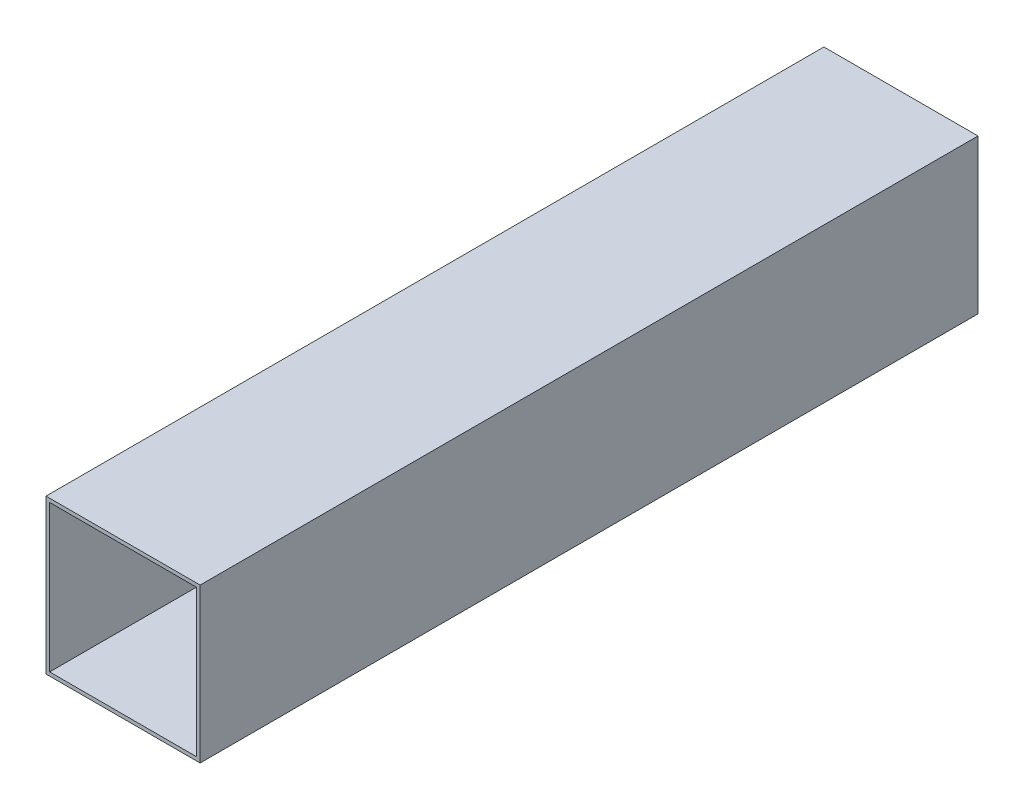
SolidWorks part; units mm, degrees
ref_plane "Front Plane" through (0, 0, 0) normal (0, 0, 1) x (1, 0, 0)
ref_plane "Top Plane" through (0, 0, 0) normal (0, 1, 0) x (1, 0, 0)
ref_plane "Right Plane" through (0, 0, 0) normal (1, 0, 0) x (0, 0, -1)
sketch "Sketch2" plane through (0, 0, 0) normal (0, 0, 1) x (1, 0, 0)
  line L1 (-50, -50) -> (50, -50)
  line L2 (-50, -50) -> (-50, 50)
  line L3 (-50, 50) -> (50, 50)
  line L4 (50, -50) -> (50, 50)
  line L5 (-50, -50) -> (50, 50) construction
  line L6 (-50, 50) -> (50, -50) construction
  line L7 (-52.5, 52.5) -> (52.5, 52.5)
  line L8 (-52.5, 52.5) -> (-52.5, -52.5)
  line L9 (-52.5, -52.5) -> (52.5, -52.5)
  line L10 (52.5, 52.5) -> (52.5, -52.5)
  line L11 (-52.5, 52.5) -> (52.5, -52.5) construction
  line L12 (-52.5, -52.5) -> (52.5, 52.5) construction
  point P0 (0, 0)
  point P6 (0, 0)
  dimension "D1" = 100
  dimension "D2" = 100
  dimension "D3" = 105
  dimension "D4" = 105
extrude "Boss-Extrude1" add sketch "Sketch2" along normal blind 530
sketch "Sketch3" plane through (0, 0, 0) normal (0, 1, 0) x (1, 0, 0)
  line L1 (35.9608, -90) -> (-34.0392, -90)
  line L2 (35.9608, -90) -> (35.9608, -150)
  line L3 (35.9608, -150) -> (-34.0392, -150)
  line L4 (-34.0392, -90) -> (-34.0392, -150)
  line L5 (35.9608, -90) -> (-34.0392, -150) construction
  line L6 (35.9608, -150) -> (-34.0392, -90) construction
  line L7 (35.9608, -300) -> (-34.0392, -300)
  line L8 (35.9608, -300) -> (35.9608, -360)
  line L9 (35.9608, -360) -> (-34.0392, -360)
  line L10 (-34.0392, -300) -> (-34.0392, -360)
  line L11 (35.9608, -300) -> (-34.0392, -360) construction
  line L12 (35.9608, -360) -> (-34.0392, -300) construction
  point P0 (0.9608, -120)
  point P5 (0.9608, -330)
  dimension "D1" = 70
  dimension "D2" = 60
  dimension "D3" = 120
  dimension "D4" = 70
  dimension "D5" = 60
  dimension "D6" = 210
extrude "Cut-Extrude1" cut sketch "Sketch3" against normal blind 530
